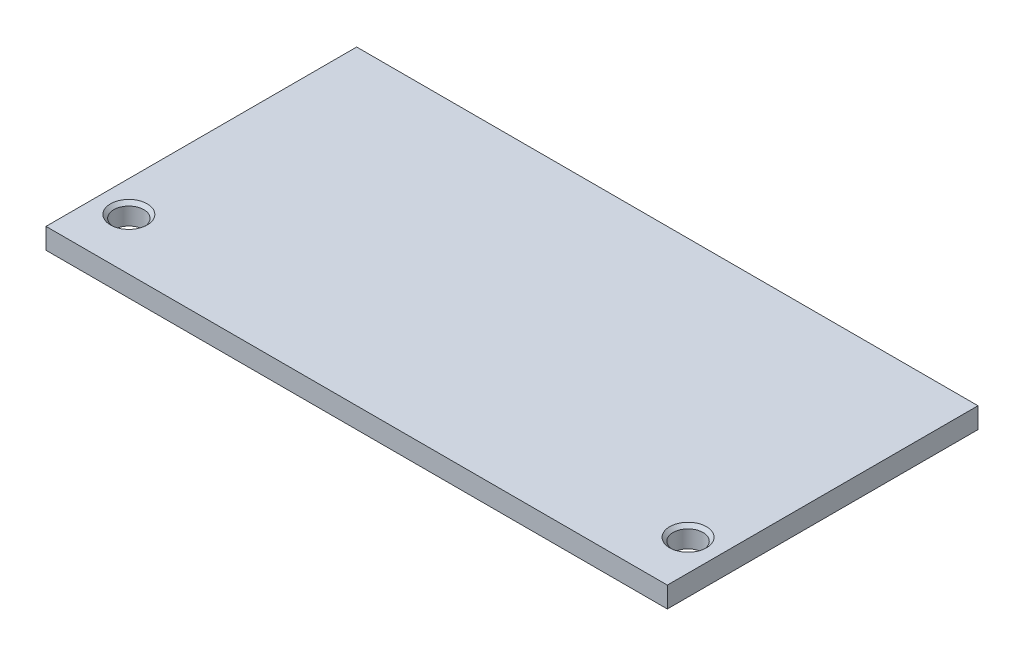
SolidWorks part; units mm, degrees
ref_plane "前视基准面" through (0, 0, 0) normal (0, 0, 1) x (1, 0, 0)
ref_plane "上视基准面" through (0, 0, 0) normal (0, 1, 0) x (1, 0, 0)
ref_plane "右视基准面" through (0, 0, 0) normal (1, 0, 0) x (0, 0, -1)
other "Configuration Table"
sketch "草图1" plane through (0, 0, 0) normal (0, 1, 0) x (1, 0, 0)
  line L1 (0, 0) -> (60, 0)
  line L2 (0, 0) -> (0, 30)
  line L3 (0, 30) -> (60, 30)
  line L4 (60, 0) -> (60, 30)
  dimension "D1" = 60
  dimension "D2" = 30
extrude "凸台-拉伸1" add sketch "草图1" along normal blind 2
sketch "草图2" plane through (0, 2, 0) normal (0, 1, 0) x (1, 0, 0)
  line L2 (0, 0) -> (3, 0) construction
  line L3 (0, 0) -> (60, 0) construction
  line L4 (3, 0) -> (3, 5) construction
  line L5 (30, 30) -> (30, 0) construction
  line L6 (60, 30) -> (0, 30) construction
  circle A0 centre (3, 5) radius 1.75
  circle A1 centre (57, 5) radius 1.75
  point P1 (3, 5)
  point P11 (57, 5)
  point P18 (3, 5)
hole_wizard "M3.5 螺纹孔1" positions "草图2" profile "草图3" tap size "M3.5" standard "GB" end condition through all
sketch "草图3" plane through (3, 2, -5) normal (1, 0, 0) x (0, 0, 1)
  line L0 (0, 0) -> (0, 2)
  line L1 (0, 2) -> (1.45, 2)
  line L2 (1.45, 2) -> (1.45, 0.325)
  line L3 (1.45, 0.325) -> (1.775, 0)
  line L5 (1.775, 0) -> (0, 0)
  line L6 (-1.45, 0.325) -> (-1.775, 0) construction
  line L11 (0, -6.35) -> (0, 107.95) construction
  dimension "通孔螺纹孔钻头直径" = 2.9
  dimension "通孔螺纹孔钻头深度" = 2
  dimension "近端锥形沉头孔直径" = 3.55
  dimension "近端锥形沉头孔角度" = 90
cosmetic thread "孔螺蚊线1" parameters "D2"=3.5
cosmetic thread "孔螺蚊线2" parameters "D2"=3.5
sketch "草图4" plane through (0, 2, 0) normal (0, 1, 0) x (1, 0, 0)
  line L0 (30, 30) -> (30, 22.75) construction
  line L1 (60, 30) -> (0, 30) construction
  circle A0 centre (30, 22.75) radius 4.5527
  dimension "D1" = 7.25
